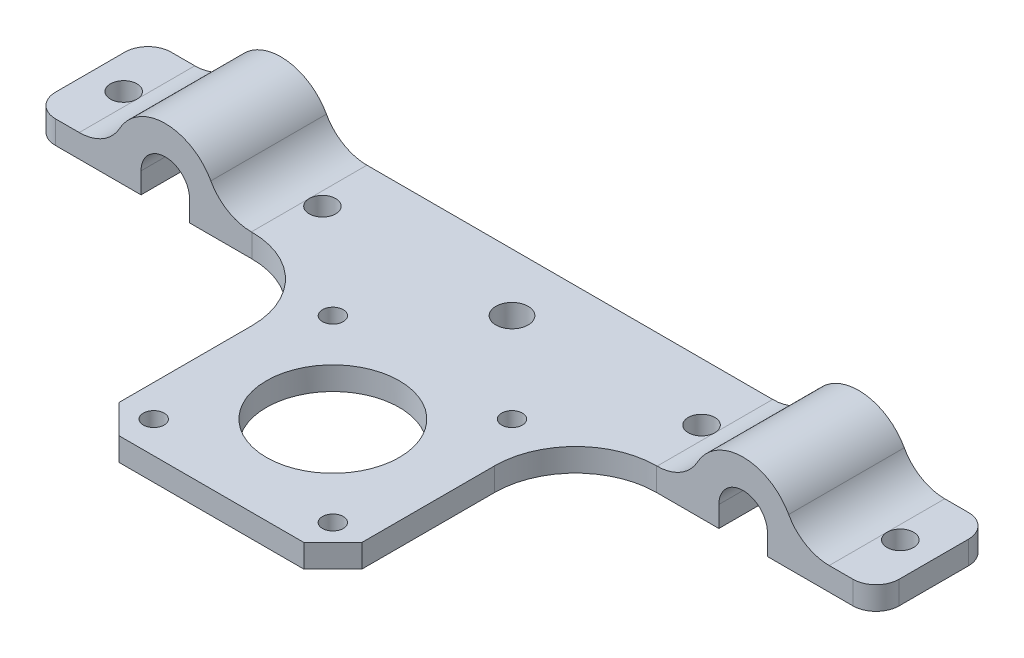
SolidWorks part; units mm, degrees
ref_plane "前视基准面" through (0, 0, 0) normal (0, 0, 1) x (1, 0, 0)
ref_plane "上视基准面" through (0, 0, 0) normal (0, 1, 0) x (1, 0, 0)
ref_plane "右视基准面" through (0, 0, 0) normal (1, 0, 0) x (0, 0, -1)
sketch "草图1" plane through (0, 0, 0) normal (0, 0, 1) x (1, 0, 0)
  line L0 (-1000, 0) -> (49000, 0) construction
  line L1 (0, -1000) -> (0, 49000) construction
  line L2 (54.2, 3.8) -> (54.2, 0.2)
  line L3 (54.2, 0.2) -> (72.9978, 0.2)
  line L4 (72.9978, 0.2) -> (72.9978, 4.2)
  line L5 (72.9978, 4.2) -> (64.8916, 4.2)
  line L6 (-35.1084, 4.2) -> (35.1084, 4.2)
  line L7 (-45.8, 0.2) -> (45.8, 0.2)
  line L8 (45.8, 0.2) -> (45.8, 3.8)
  line L9 (1000, 0) -> (-49000, 0) construction
  line L10 (-45.8, 0.2) -> (-45.8, 3.8)
  line L11 (-72.9978, 4.2) -> (-64.8916, 4.2)
  line L12 (-72.9978, 0.2) -> (-72.9978, 4.2)
  line L13 (-54.2, 0.2) -> (-72.9978, 0.2)
  line L14 (-54.2, 3.8) -> (-54.2, 0.2)
  circle A0 centre (50, 4) radius 4 construction
  arc A1 (54.2, 3.8) -> (45.8, 3.8) centre (50, 3.8) ccw
  circle A2 centre (-50, 4) radius 4 construction
  arc A3 (57.8838, 8.3412) -> (42.1162, 8.3412) centre (50, 4) ccw
  arc A4 (-57.8838, 8.3412) -> (-42.1162, 8.3412) centre (-50, 4) cw
  arc A5 (-54.2, 3.8) -> (-45.8, 3.8) centre (-50, 3.8) cw
  arc A6 (-42.1162, 8.3412) -> (-35.1084, 4.2) centre (-35.1084, 12.2) ccw
  arc A7 (-57.8838, 8.3412) -> (-64.8916, 4.2) centre (-64.8916, 12.2) cw
  arc A8 (35.1084, 4.2) -> (42.1162, 8.3412) centre (35.1084, 12.2) ccw
  arc A9 (64.8916, 4.2) -> (57.8838, 8.3412) centre (64.8916, 12.2) cw
  point P17 (0, 4.2)
  point P28 (0, 0.2)
  point P33 (-41.0022, 4.2)
  point P36 (-58.9978, 4.2)
  point P39 (41.0022, 4.2)
  point P42 (58.9978, 4.2)
  dimension "D1" = 8
  dimension "D2" = 8.4
  dimension "D3" = 9
  dimension "D8" = 8
  dimension "D4" = 0.2
  dimension "D5" = 4
  dimension "D6" = 14
  dimension "D7" = 100
extrude "凸台-拉伸1" add sketch "草图1" along normal blind 20
fillet "圆角1" radius 4 4 edges at (72.9978, 2.2, 20) (72.9978, 2.2, 0) (-72.9978, 2.2, 0) (-72.9978, 2.2, 20)
sketch "草图3" plane through (0, 0, 20) normal (0, 0, 1) x (1, 0, 0)
  line L0 (0, 0) -> (0, 4.2) construction
  line L1 (35.1084, 4.2) -> (-35.1084, 4.2) construction
  line L2 (-45.8, 0.2) -> (45.8, 0.2) construction
  line L3 (-21, 4.2) -> (21, 4.2)
  line L4 (-21, 4.2) -> (-21, 0.2)
  line L5 (-21, 0.2) -> (21, 0.2)
  line L6 (21, 4.2) -> (21, 0.2)
  dimension "D1" = 42
extrude "凸台-拉伸2" add sketch "草图3" along normal blind 42
fillet "圆角2" radius 14 2 edges at (21, 2.2, 20) (-21, 2.2, 20)
chamfer "倒角1" distance 5 angle 45 2 edges at (21, 2.2, 62) (-21, 2.2, 62)
sketch "草图2" plane through (0, 4.2, 0) normal (0, 1, 0) x (1, 0, 0)
  line L0 (0, -1000) -> (0, 49000) construction
  line L1 (35.1084, 0) -> (-35.1084, 0) construction
  line L2 (50, -1000) -> (50, 49000) construction
  line L3 (57.8838, 0) -> (42.1162, 0) construction
  line L4 (35.1084, -20) -> (35, -20) construction
  line L5 (72.9978, -16) -> (72.9978, -4) construction
  circle A0 centre (0, -10) radius 2.8
  circle A1 centre (67.1978, -10) radius 2.3
  circle A2 centre (32.8022, -10) radius 2.3
  circle A3 centre (-32.8022, -10) radius 2.3
  circle A4 centre (-67.1978, -10) radius 2.3
  circle A5 centre (0, -41) radius 11.5
  circle A6 centre (15.5, -25.5) radius 1.8
  circle A7 centre (15.5, -56.5) radius 1.8
  circle A8 centre (-15.5, -56.5) radius 1.8
  circle A9 centre (-15.5, -25.5) radius 1.8
  point P7 (0, 0)
  point P12 (50, 0)
  point P38 (0, -41)
  dimension "D1" = 5.6
  dimension "D3" = 4.6
  dimension "D5" = 23
  dimension "D9" = 3.6
  dimension "D2" = 10
  dimension "D4" = 5.8
  dimension "D6" = 21
  dimension "D7" = 15.5
  dimension "D8" = 15.5
  dimension "D10" = 4
extrude "切除-拉伸1" cut sketch "草图2" against normal through all and the other way through all
